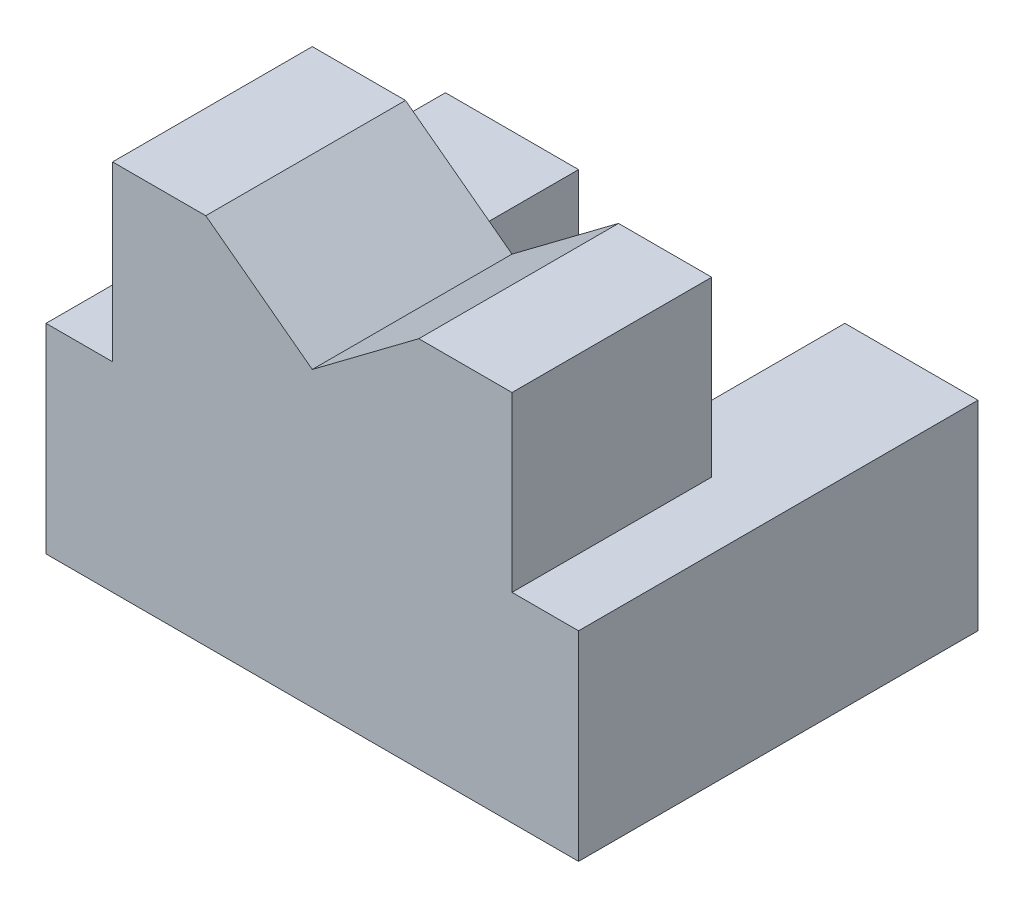
SolidWorks part; units mm, degrees
ref_plane "前视基准面" through (0, 0, 0) normal (0, 0, 1) x (1, 0, 0)
ref_plane "上视基准面" through (0, 0, 0) normal (0, 1, 0) x (1, 0, 0)
ref_plane "右视基准面" through (0, 0, 0) normal (1, 0, 0) x (0, 0, -1)
other "Configuration Table"
sketch "Sketch1" plane through (0, 0, 0) normal (0, 0, 1) x (1, 0, 0)
  line L1 (0, 0) -> (30, 0)
  line L2 (0, 0) -> (0, -28)
  line L3 (0, -28) -> (30, -28)
  line L4 (30, 0) -> (30, -28)
  line L5 (15, 0) -> (15, -28) construction
  dimension "D1" = 30
  dimension "D2" = 28
extrude "Boss-Extrude1" add sketch "Sketch1" against normal blind 15 contours L1 L4 L3 L2
sketch "Sketch2" plane through (0, 0, 0) normal (0, 0, 1) x (1, 0, 0)
  line L0 (0, 0) -> (30, 0) construction
  line L1 (23, 0) -> (15, -6)
  line L2 (15, -6) -> (7, 0)
  line L3 (7, 0) -> (23, 0)
  point P0 (15, -6)
  point P1 (23, 0)
  point P2 (7, 0)
  point P5 (23, 0)
  dimension "D1" = 16
  dimension "D2" = 6
  dimension "D3" = 7
extrude "Cut-Extrude4" cut sketch "Sketch2" against normal through all contours L3 L1 L2
sketch "Sketch3" plane through (0, 0, 0) normal (0, 0, 1) x (1, 0, 0)
  line L0 (15, -28) -> (5, -28)
  line L1 (0, -28) -> (30, -28) construction
  line L2 (15, -28) -> (25, -28)
  line L4 (5, -28) -> (-5, -28)
  line L5 (5, -28) -> (5, -13)
  line L6 (5, -13) -> (-5, -13)
  line L7 (-5, -28) -> (-5, -13)
  line L8 (25, -28) -> (35, -28)
  line L9 (25, -28) -> (25, -13)
  line L10 (25, -13) -> (35, -13)
  line L11 (35, -28) -> (35, -13)
  line M5 (0, 0) -> (0, -28)
  line M6 (0, -28) -> (30, -28)
  line M7 (30, -28) -> (30, 0)
  dimension "D1" = 20
  dimension "D2" = 10
  dimension "D3" = 15
  dimension "D4" = 10
  dimension "D5" = 15
  dimension "D6" = 10
extrude "凸台-拉伸3" add sketch "Sketch3" against normal blind 30 contours L7 L4 L6 M5 | L5 L6 M5 M6 | L10 L9 M6 M7 | L8 L11 L10 M7
